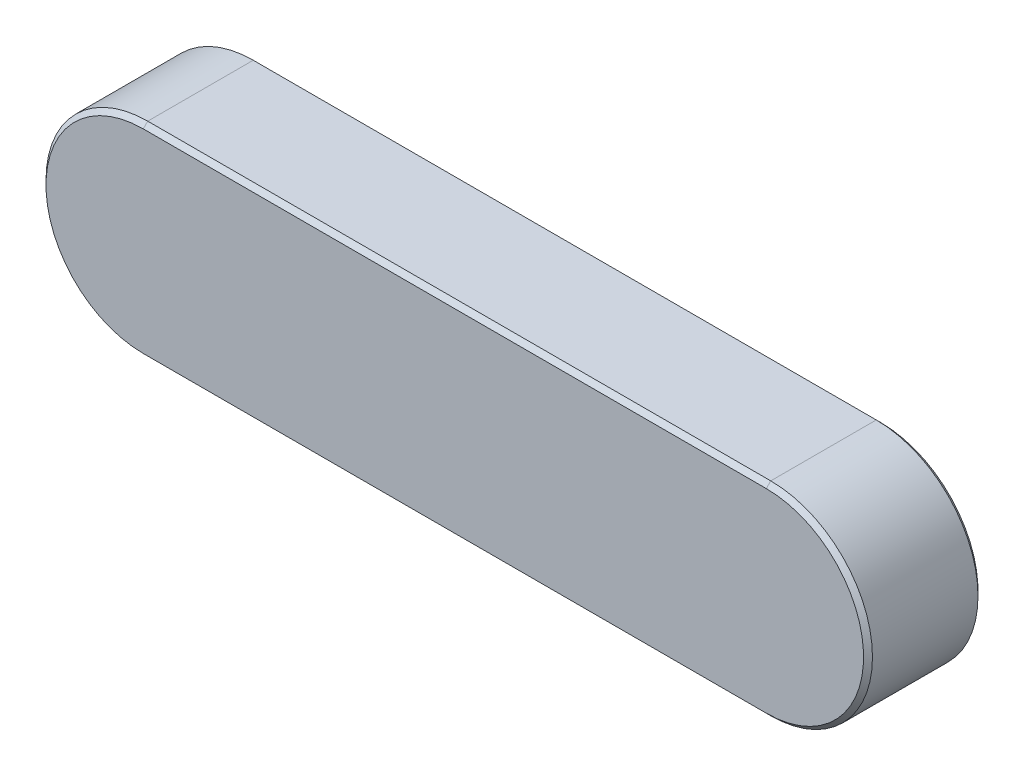
SolidWorks part; units mm, degrees
ref_plane "Piano frontale" through (0, 0, 0) normal (0, 0, 1) x (1, 0, 0)
ref_plane "Piano superiore" through (0, 0, 0) normal (0, 1, 0) x (1, 0, 0)
ref_plane "Piano destro" through (0, 0, 0) normal (1, 0, 0) x (0, 0, -1)
sketch "Schizzo1" plane through (0, 0, 0) normal (0, 0, 1) x (1, 0, 0)
  line L0 (0, 0) -> (98, 0) construction
  line L1 (0, 16) -> (98, 16)
  line L2 (0, -16) -> (98, -16)
  arc A0 (0, 16) -> (0, -16) centre (0, 0) ccw
  arc A1 (98, -16) -> (98, 16) centre (98, 0) ccw
  point P3 (49, 0)
  dimension "D1" = 98
  dimension "D2" = 32
extrude "Estrusione-Estrusione1" add sketch "Schizzo1" along normal blind 18
chamfer "Smusso1" distance 0.7 angle 45 8 edges at (-16, 0, 18) (49, -16, 18) (114, 0, 18) (49, 16, 18) (114, 0, 0) (49, 16, 0) (-16, 0, 0) (49, -16, 0)
